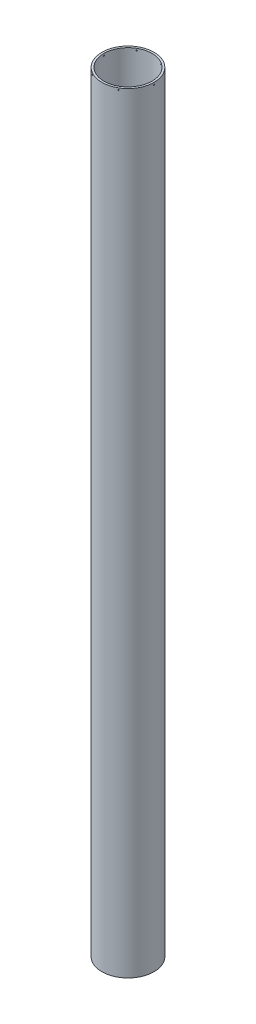
SolidWorks part; units mm, degrees
material "S-Glass Fiber"
ref_plane "Front Plane" through (0, 0, 0) normal (0, 0, 1) x (1, 0, 0)
ref_plane "Top Plane" through (0, 0, 0) normal (0, 1, 0) x (1, 0, 0)
ref_plane "Right Plane" through (0, 0, 0) normal (1, 0, 0) x (0, 0, -1)
sketch "Sketch1" plane through (0, 0, 0) normal (0, 1, 0) x (1, 0, 0)
  circle A0 centre (0, 0) radius 82.55
  circle A1 centre (0, 0) radius 76.2
  dimension "D1" = 152.4
  dimension "D2" = 6.35
extrude "Boss-Extrude1" add sketch "Sketch1" along normal mid plane 2438.4
sketch "Sketch2" plane through (0, 0, 0) normal (1, 0, 0) x (0, 0, -1)
  line L0 (-82.55, 1219.2) -> (82.55, 1219.2) construction
  circle A0 centre (0, 1212.85) radius 1.5875
  point P4 (0, 0)
  dimension "D1" = 3.175
  dimension "D2" = 6.35
extrude "Cut-Extrude1" cut sketch "Sketch2" against normal through all
pattern_circular "CirPattern1" count 6 over 360 about axis through (0, 1219.2, 0) along (0, 1, 0) of "Cut-Extrude1"
